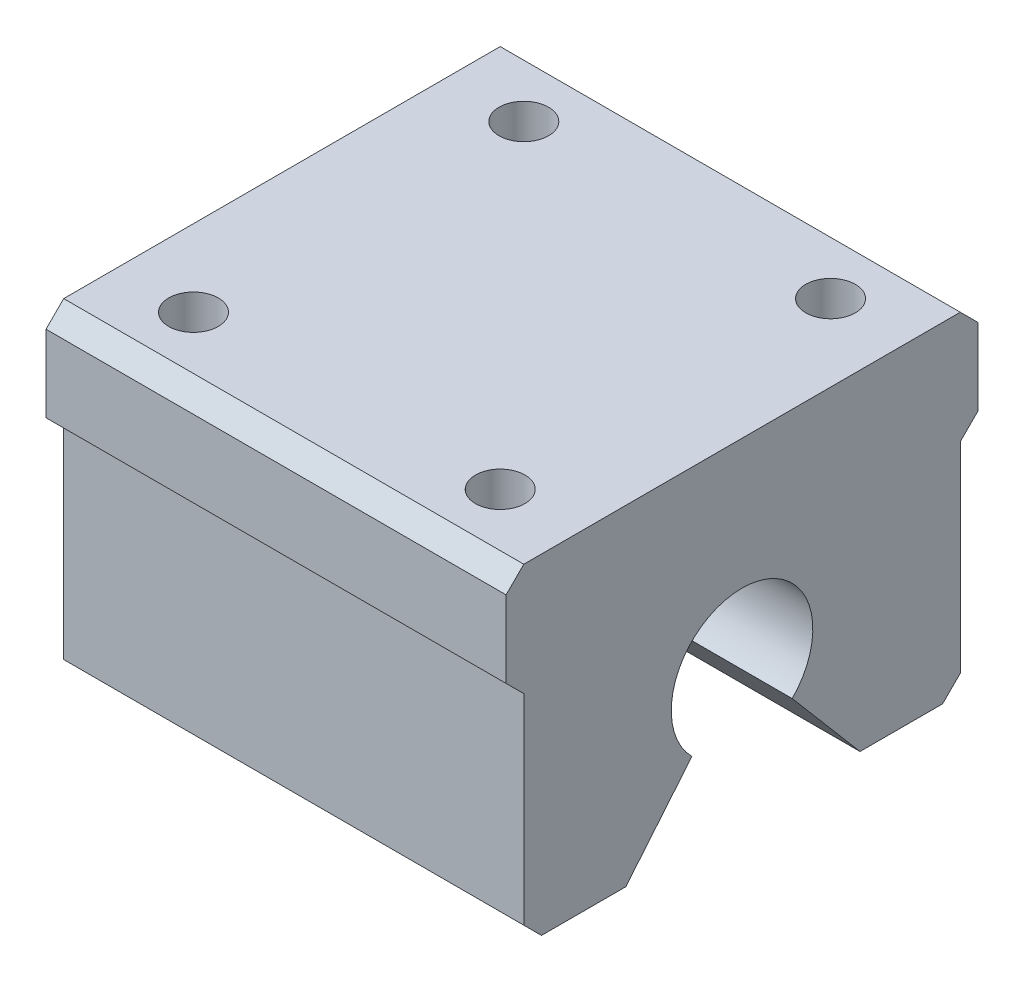
SolidWorks part; units mm, degrees
ref_plane "Plan de face" through (0, 0, 0) normal (0, 0, 1) x (1, 0, 0)
ref_plane "Plan de dessus" through (0, 0, 0) normal (0, 1, 0) x (1, 0, 0)
ref_plane "Plan de droite" through (0, 0, 0) normal (1, 0, 0) x (0, 0, -1)
sketch "Esquisse1" plane through (0, 0, 0) normal (0, 1, 0) x (1, 0, 0)
  line L1 (-12.9498, 12.5178) -> (26.0502, 12.5178)
  line L2 (-12.9498, 12.5178) -> (-12.9498, -27.4822)
  line L3 (-12.9498, -27.4822) -> (26.0502, -27.4822)
  line L4 (26.0502, 12.5178) -> (26.0502, -27.4822)
  dimension "D1" = 39
  dimension "D2" = 40
extrude "Extrusion1" add sketch "Esquisse1" along normal blind 9.5
chamfer "Chanfrein1" distance 1.5 angle 45 4 edges at (6.5502, 0, -12.5178) (6.5502, 0, 27.4822) (6.5502, 9.5, 27.4822) (6.5502, 9.5, -12.5178)
sketch "Esquisse5" plane through (0, 0, 0) normal (0, -1, 0) x (1, 0, 0)
  line L0 (-12.9498, -11.0178) -> (-12.9498, 25.9822)
  line L1 (-12.9498, -11.0178) -> (-12.9498, 25.9822) construction
  line L2 (-12.9498, 25.9822) -> (26.0502, 25.9822)
  line L3 (26.0502, 25.9822) -> (26.0502, -11.0178)
  line L4 (26.0502, -11.0178) -> (-12.9498, -11.0178)
extrude "Extrusion2" add sketch "Esquisse5" along normal blind 18.5
chamfer "Chanfrein2" distance 1.5 angle 45 2 edges at (6.5502, -18.5, 25.9822) (6.5502, -18.5, -11.0178)
sketch "Esquisse6" plane through (0, 0, -11.0178) normal (0, 0, -1) x (-1, 0, 0)
  line L0 (12.9498, -17) -> (12.9498, 0) construction
  line L1 (12.9498, -18.5) -> (-26.0502, -18.5) construction
  circle A0 centre (-6.0502, -9) radius 2.75
  dimension "D3" = 5.5
  dimension "D1" = 19
  dimension "D2" = 9.5
extrude "Extrusion3" cut sketch "Esquisse6" against normal blind 5
chamfer "Chanfrein3" distance 1 angle 45 1 edges at (3.3002, -9, -11.0178)
hole_wizard "Trou taraudé M5x0.81" positions "Esquisse3D1" profile "Esquisse7" tap size "M5x0.8" standard "Ansi Metric"
sketch3d "Esquisse3D1"
  line L0 (-12.9498, 9.5, -11.0178) -> (-12.9498, 9.5, 25.9822) construction
  line L3 (26.0502, 9.5, -11.0178) -> (-12.9498, 9.5, -11.0178) construction
  point P0 (-6.4498, 9.5, -6.5178)
  point P2 (19.5502, 9.5, -6.5178)
  point P4 (19.5502, 9.5, 21.4822)
  point P6 (-6.4498, 9.5, 21.4822)
  dimension "D1" = 26
  dimension "D2" = 28
  dimension "D3" = 6.5
  dimension "D4" = 4.5
sketch "Esquisse7" plane through (-6.4498, 9.5, -6.5178) normal (1, 0, 0) x (0, 0, 1)
  line L0 (0, 0) -> (0, 13.6618)
  line L1 (0, 13.6618) -> (2.1, 12.4)
  line L2 (2.1, 12.4) -> (2.1, 0)
  line L5 (2.1, 0) -> (0, 0)
  line L10 (0, 13.6618) -> (-2.1, 12.4) construction
  line L11 (0, -6.35) -> (0, 107.95) construction
  dimension "Diamètre du trou pour taraudage" = 4.2
  dimension "Profondeur du trou pour taraudage" = 12.4
  dimension "Angle de pointe" = 118
sketch "Esquisse8" plane through (-12.9498, 0, 0) normal (-1, 0, 0) x (0, 0, 1)
  line L0 (-11.0178, 9.5) -> (25.9822, 9.5) construction
  line L1 (27.4822, 8) -> (27.4822, 1.5) construction
  line L2 (3.2322, -11.7353) -> (-2.5178, -18.5)
  line L3 (11.7322, -11.7353) -> (17.3356, -18.5)
  line L4 (24.4822, -18.5) -> (-9.5178, -18.5) construction
  line L5 (17.3356, -18.5) -> (-2.5178, -18.5)
  arc A0 (11.7322, -11.7353) -> (3.2322, -11.7353) centre (7.4822, -7.5) ccw
  dimension "D3" = 12
  dimension "D1" = 17
  dimension "D2" = 20
  dimension "D4" = 80
  dimension "D6" = 8.5
extrude "Extrusion4" cut sketch "Esquisse8" against normal through all
